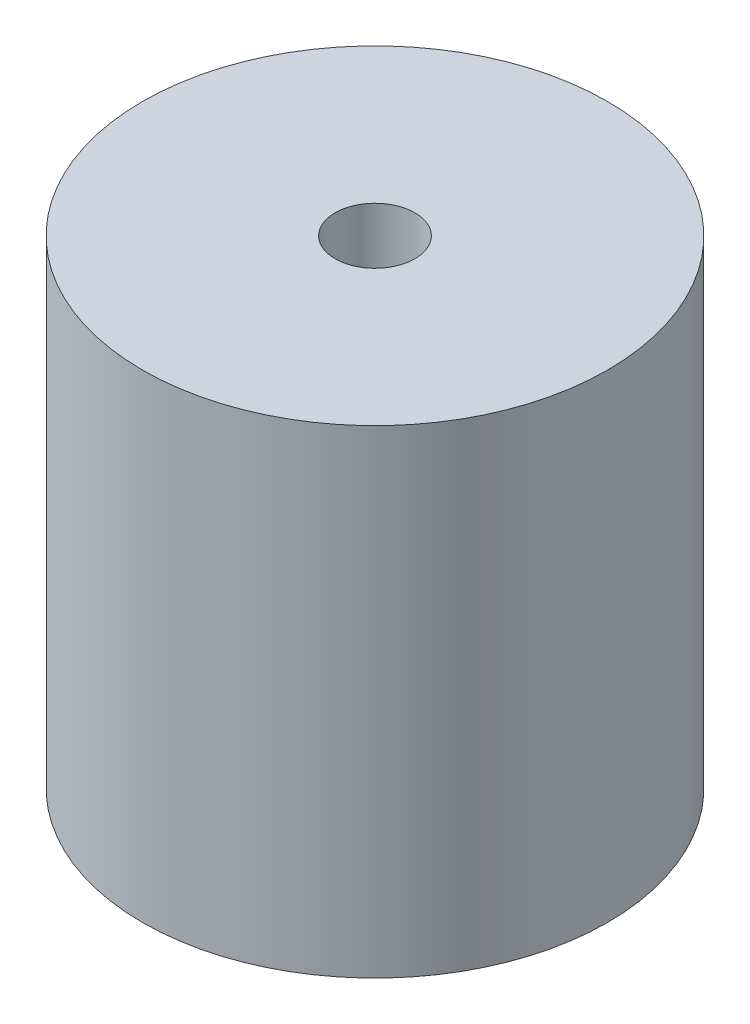
SolidWorks part; units mm, degrees
ref_plane "Plan de face" through (0, 0, 0) normal (0, 0, 1) x (1, 0, 0)
ref_plane "Plan de dessus" through (0, 0, 0) normal (0, 1, 0) x (1, 0, 0)
ref_plane "Plan de droite" through (0, 0, 0) normal (1, 0, 0) x (0, 0, -1)
sketch "Esquisse1" plane through (0, 0, 0) normal (0, 1, 0) x (1, 0, 0)
  circle A0 centre (0, 0) radius 17.5
  dimension "D1" = 35
extrude "Boss.-Extru.1" add sketch "Esquisse1" along normal blind 36
sketch "Esquisse2" plane through (0, 36, 0) normal (0, 1, 0) x (1, 0, 0)
  circle A0 centre (0, 0) radius 3
  dimension "D1" = 6
extrude "Enlèv. mat.-Extru.1" cut sketch "Esquisse2" against normal through all
